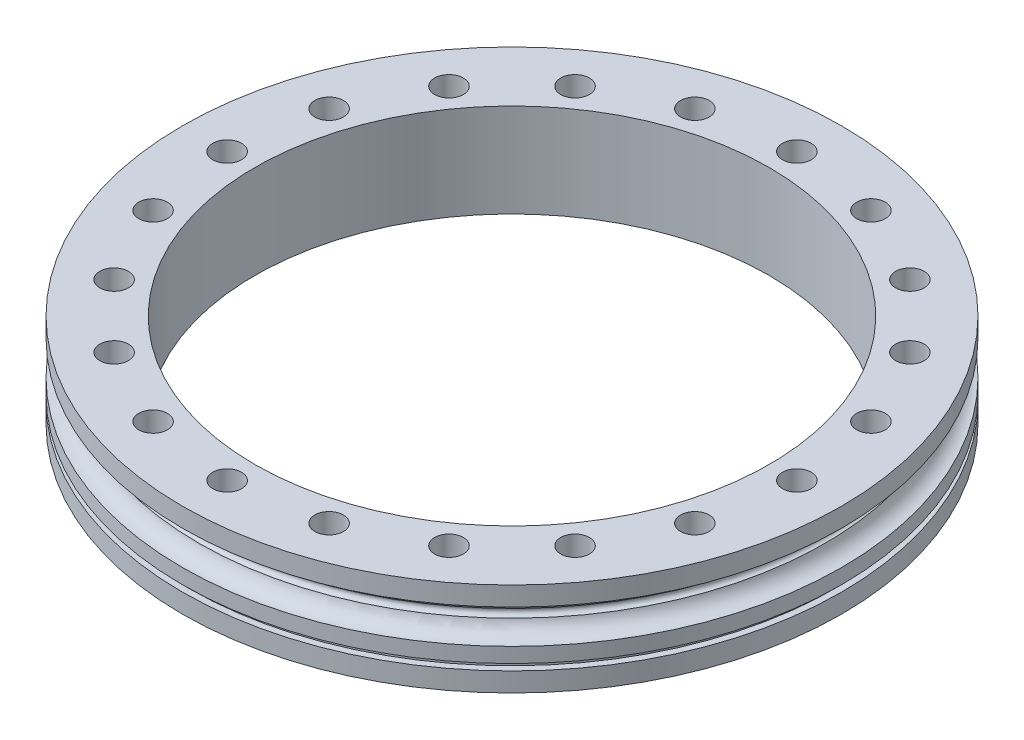
SolidWorks part; units mm, degrees
ref_plane "Plan de face" through (0, 0, 0) normal (0, 0, 1) x (1, 0, 0)
ref_plane "Plan de dessus" through (0, 0, 0) normal (0, 1, 0) x (1, 0, 0)
ref_plane "Plan de droite" through (0, 0, 0) normal (1, 0, 0) x (0, 0, -1)
sketch "Esquisse1" plane through (0, 0, 0) normal (0, 0, 1) x (1, 0, 0)
  line L0 (0, 0) -> (-193, 0) construction
  line L1 (-193, 0) -> (-193, 44) construction
  line L2 (-193, 44) -> (0, 44) construction
  line L3 (0, 44) -> (0, 0) construction
  line L4 (-193, 0) -> (-157, 0) construction
  line L5 (-157, 0) -> (-157, 7) construction
  line L6 (-157, 7) -> (-157, 23) construction
  line L7 (-157, 44) -> (-157, 35) construction
  line L8 (-157, 44) -> (-193, 44) construction
  line L9 (-157, 15) -> (-164.5, 15) construction
  line L10 (-164.5, 15) -> (-166.5, 15) construction
  line L11 (-157, 35) -> (-160, 35) construction
  line L12 (-160, 35) -> (-160, 32) construction
  line L13 (-160, 32) -> (-157, 32) construction
  line L14 (-157, 32) -> (-157, 23) construction
  line L15 (-157, 35) -> (-157, 32) construction
  line L16 (-156, 44) -> (-156, 0) construction
  line L17 (-155, 23) -> (-155, 32)
  line L18 (-155, 32) -> (-121, 32)
  line L19 (-121, 32) -> (-121, -12)
  line L20 (-121, -12) -> (-155, -12)
  line L21 (-155, -12) -> (-155, -3)
  line L22 (-155, -3) -> (-155, 0) construction
  line L23 (-155, 0) -> (-155, 7)
  line L24 (-155, 0) -> (-152, 0)
  line L25 (-152, 0) -> (-152, -3)
  line L26 (-152, -3) -> (-155, -3)
  line L27 (-157, 32) -> (-155, 32) construction
  arc A0 (-157, 23) -> (-157, 7) centre (-157, 15) ccw construction
  arc A1 (-164.75, 16.9843) -> (-164.75, 13.0157) centre (-164.5, 15) ccw construction
  arc A2 (-164.75, 13.0157) -> (-157, 7) centre (-157, 15) ccw construction
  arc A3 (-157, 23) -> (-164.75, 16.9843) centre (-157, 15) ccw construction
  arc A4 (-147.25, 16.9843) -> (-147.25, 13.0157) centre (-147.5, 15) cw
  arc A5 (-155, 23) -> (-155, 7) centre (-155, 15) cw construction
  arc A6 (-155, 23) -> (-147.25, 16.9843) centre (-155, 15) cw
  arc A7 (-147.25, 13.0157) -> (-155, 7) centre (-155, 15) cw
  dimension "D7" = 8
  dimension "D8" = 7.5
  dimension "D9" = 2
  dimension "D2" = 44
  dimension "D3" = 15
  dimension "D4" = 12
  dimension "D5" = 3
  dimension "D6" = 3
  dimension "D10" = 193
  dimension "D11" = 1
  dimension "D12" = 3
  dimension "D13" = 3
  dimension "D14" = 44
  dimension "D15" = 242
  dimension "D16" = 157
revolve "Révolution1" add sketch "Esquisse1" angle 360 about L3
sketch "Esquisse4" plane through (0, 32, 0) normal (0, 1, 0) x (1, 0, 0)
  line L0 (0, 0) -> (-134, 0) construction
  line L1 (0, 0) -> (-127.4416, 41.4083) construction
  circle A0 centre (-134, 0) radius 6.75
  circle A1 centre (-127.4416, 41.4083) radius 6.75
  circle A2 centre (-108.4083, 78.7632) radius 6.75
  circle A3 centre (-78.7632, 108.4083) radius 6.75
  circle A4 centre (-41.4083, 127.4416) radius 6.75
  circle A5 centre (0, 134) radius 6.75
  circle A6 centre (41.4083, 127.4416) radius 6.75
  circle A7 centre (78.7632, 108.4083) radius 6.75
  circle A8 centre (108.4083, 78.7632) radius 6.75
  circle A9 centre (127.4416, 41.4083) radius 6.75
  circle A10 centre (134, 0) radius 6.75
  circle A11 centre (127.4416, -41.4083) radius 6.75
  circle A12 centre (108.4083, -78.7632) radius 6.75
  circle A13 centre (78.7632, -108.4083) radius 6.75
  circle A14 centre (41.4083, -127.4416) radius 6.75
  circle A15 centre (0, -134) radius 6.75
  circle A16 centre (-41.4083, -127.4416) radius 6.75
  circle A17 centre (-78.7632, -108.4083) radius 6.75
  circle A18 centre (-108.4083, -78.7632) radius 6.75
  circle A19 centre (-127.4416, -41.4083) radius 6.75
  point P38 (0, 0)
  point P47 (0, 0)
  dimension "D1" = 13.5
  dimension "D2" = 134
  dimension "D4" = 18
  dimension "D5" = 134
  dimension "D3" = 20
extrude "Enlèv. mat.-Extru.2" cut sketch "Esquisse4" against normal through all
